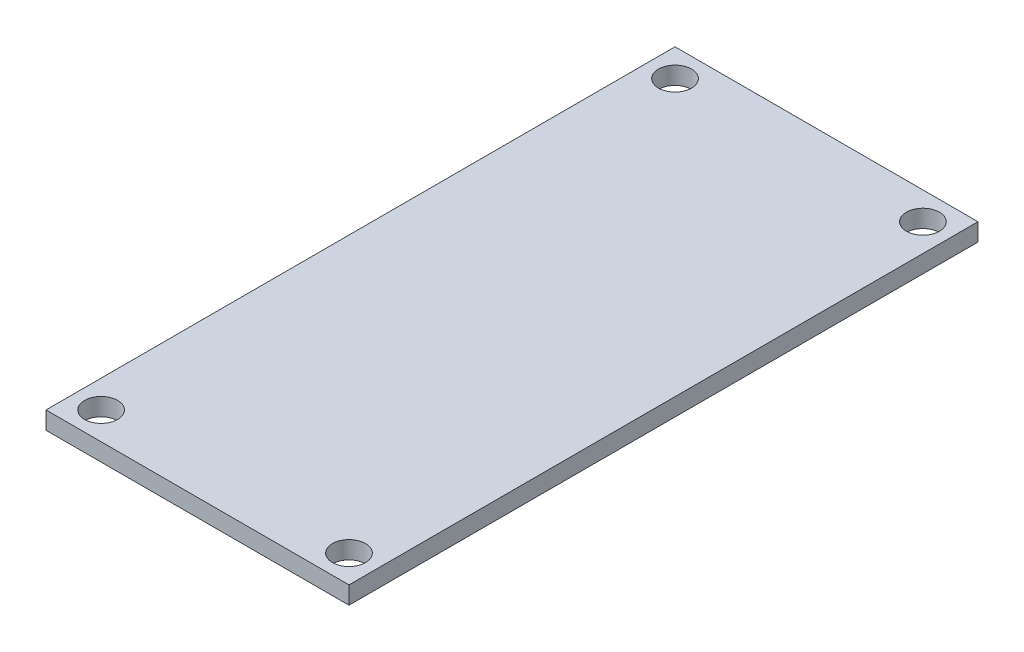
SolidWorks part; units mm, degrees
ref_plane "Front Plane" through (0, 0, 0) normal (0, 0, 1) x (1, 0, 0)
ref_plane "Top Plane" through (0, 0, 0) normal (0, 1, 0) x (1, 0, 0)
ref_plane "Right Plane" through (0, 0, 0) normal (1, 0, 0) x (0, 0, -1)
sketch "Sketch1" plane through (0, 0, 0) normal (0, 1, 0) x (1, 0, 0)
  line L0 (-55, 0) -> (55, 0) construction
  line L1 (-13.75, -28.545) -> (13.75, -28.545)
  line L2 (-13.75, -28.545) -> (-13.75, 28.545)
  line L3 (-13.75, 28.545) -> (13.75, 28.545)
  line L4 (13.75, -28.545) -> (13.75, 28.545)
  line L5 (-13.75, -28.545) -> (13.75, 28.545) construction
  line L6 (-13.75, 28.545) -> (13.75, -28.545) construction
  line L7 (0, -55) -> (0, 55) construction
  circle A0 centre (-11.25, 26.045) radius 1.5
  circle A1 centre (-11.25, -26.045) radius 1.5
  circle A2 centre (11.25, 26.045) radius 1.5
  circle A3 centre (11.25, -26.045) radius 1.5
  point P0 (0, 0)
  dimension "D3" = 3
  dimension "D1" = 57.09
  dimension "D2" = 27.5
  dimension "D4" = 2.5
  dimension "D5" = 2.5
extrude "Boss-Extrude1" add sketch "Sketch1" along normal blind 1.6
